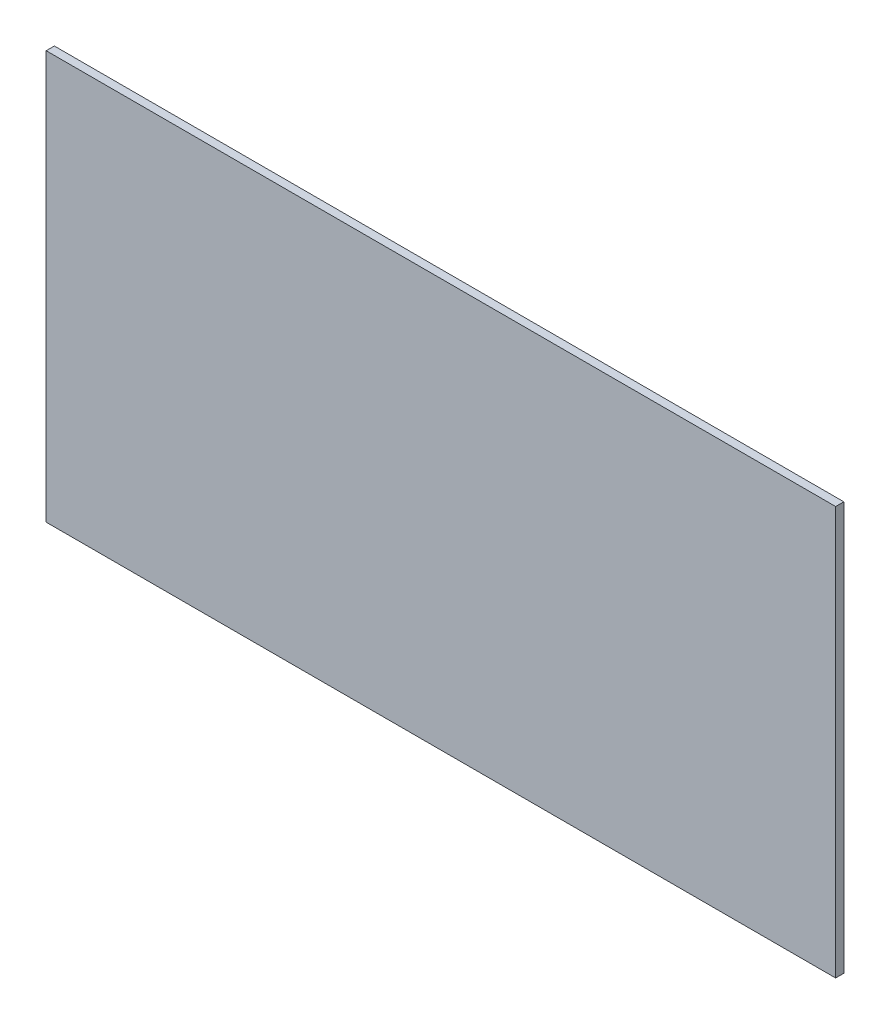
SolidWorks part; units mm, degrees
material "Acrylic (Medium-high impact)"
ref_plane "Front Plane" through (0, 0, 0) normal (0, 0, 1) x (1, 0, 0)
ref_plane "Top Plane" through (0, 0, 0) normal (0, 1, 0) x (1, 0, 0)
ref_plane "Right Plane" through (0, 0, 0) normal (1, 0, 0) x (0, 0, -1)
sketch "Sketch1" plane through (0, 0, 0) normal (0, 0, 1) x (1, 0, 0)
  line L1 (-145, 75) -> (145, 75)
  line L2 (-145, 75) -> (-145, -75)
  line L3 (-145, -75) -> (145, -75)
  line L4 (145, 75) -> (145, -75)
  line L5 (-145, 75) -> (145, -75) construction
  line L6 (-145, -75) -> (145, 75) construction
  point P0 (0, 0)
  dimension "D1" = 290
  dimension "D2" = 150
extrude "Boss-Extrude1" add sketch "Sketch1" along normal blind 3
